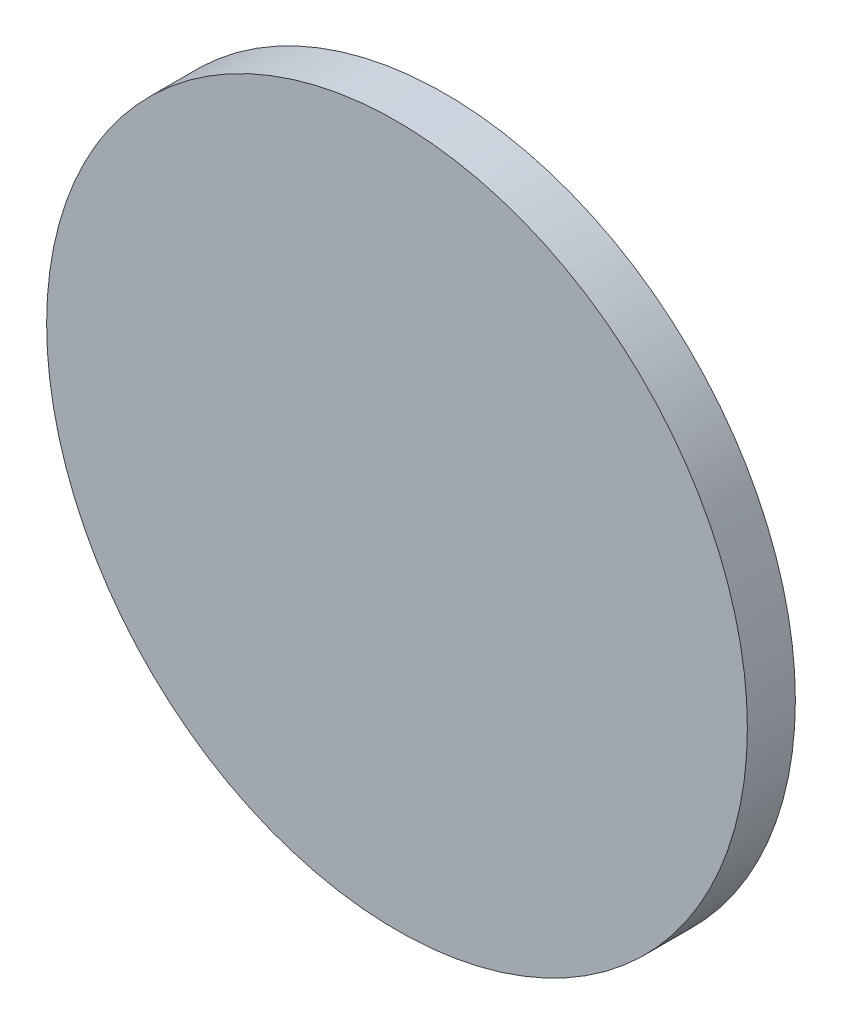
SolidWorks part; units mm, degrees
ref_plane "Front Plane" through (0, 0, 0) normal (0, 0, 1) x (1, 0, 0)
ref_plane "Top Plane" through (0, 0, 0) normal (0, 1, 0) x (1, 0, 0)
ref_plane "Right Plane" through (0, 0, 0) normal (1, 0, 0) x (0, 0, -1)
sketch "Sketch1" plane through (0, 0, 0) normal (0, 0, 1) x (1, 0, 0)
  circle A0 centre (0, 0) radius 11.675
  dimension "D1" = 23.35
extrude "Boss-Extrude1" add sketch "Sketch1" along normal mid plane 1.6
